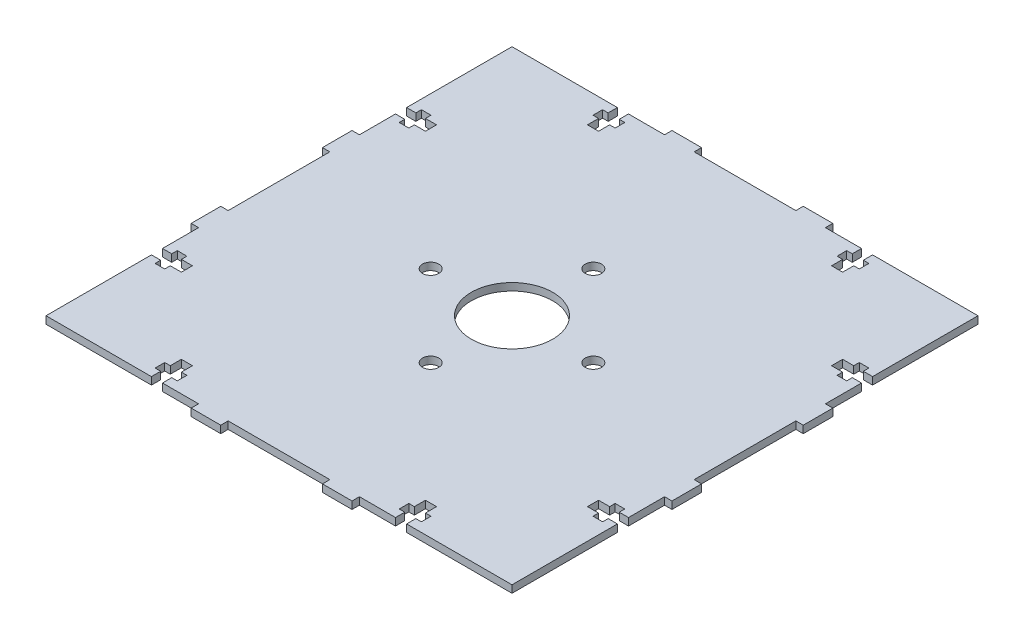
SolidWorks part; units mm, degrees
ref_plane "前视基准面" through (0, 0, 0) normal (0, 0, 1) x (1, 0, 0)
ref_plane "上视基准面" through (0, 0, 0) normal (0, 1, 0) x (1, 0, 0)
ref_plane "右视基准面" through (0, 0, 0) normal (1, 0, 0) x (0, 0, -1)
sketch "草图1" plane through (0, 0, 0) normal (0, 1, 0) x (1, 0, 0)
  line L529 (159.7547, 48.9956) -> (150.0047, 48.9956)
  line L530 (147.0047, 46.4956) -> (145.5047, 46.4956)
  line L531 (150.0047, 46.4956) -> (151.5047, 46.4956)
  line L532 (150.0047, 48.9956) -> (150.0047, 46.4956)
  line L533 (145.5047, 46.4956) -> (145.5047, 43.8956)
  line L534 (145.5047, 43.8956) -> (147.0047, 43.8956)
  line L535 (147.0047, 43.8956) -> (147.0047, 40.8956)
  line L536 (150.0047, 40.8956) -> (147.0047, 40.8956)
  line L537 (150.0047, 43.8956) -> (150.0047, 40.8956)
  line L538 (151.5047, 43.8956) -> (150.0047, 43.8956)
  line L539 (151.5047, 46.4956) -> (151.5047, 43.8956)
  line L540 (147.0047, 46.4956) -> (147.0047, 48.9956)
  line L541 (213.0047, 48.9956) -> (203.2547, 48.9956)
  line L542 (211.5047, 46.4956) -> (211.5047, 43.8956)
  line L543 (216.0047, 46.4956) -> (216.0047, 48.9956)
  line L544 (211.5047, 43.8956) -> (213.0047, 43.8956)
  line L545 (213.0047, 43.8956) -> (213.0047, 40.8956)
  line L546 (213.0047, 40.8956) -> (216.0047, 40.8956)
  line L547 (216.0047, 43.8956) -> (216.0047, 40.8956)
  line L548 (217.5047, 43.8956) -> (216.0047, 43.8956)
  line L549 (217.5047, 46.4956) -> (217.5047, 43.8956)
  line L550 (213.0047, 48.9956) -> (213.0047, 46.4956)
  line L551 (213.0047, 46.4956) -> (211.5047, 46.4956)
  line L552 (216.0047, 46.4956) -> (217.5047, 46.4956)
  line L554 (203.2547, 48.9956) -> (203.2547, 50.9956)
  line L555 (195.2547, 50.9956) -> (195.2547, 48.9956)
  line L556 (195.2547, 48.9956) -> (167.7547, 48.9956)
  line L557 (159.7547, 50.9956) -> (167.7547, 50.9956)
  line L558 (167.7547, 48.9956) -> (167.7547, 50.9956)
  line L559 (159.7547, 50.9956) -> (159.7547, 48.9956)
  line L560 (203.2547, 50.9956) -> (195.2547, 50.9956)
  line L598 (217.0047, 48.9956) -> (216.0047, 48.9956)
  line L602 (244.5047, 7.7456) -> (244.5047, 17.4956)
  line L603 (242.0047, 20.4956) -> (242.0047, 21.9956)
  line L604 (147.0047, 48.9956) -> (138.6047, 48.9956)
  line L605 (242.0047, 17.4956) -> (242.0047, 15.9956)
  line L606 (244.5047, 17.4956) -> (242.0047, 17.4956)
  line L607 (181.5047, -77.0044) -> (181.5047, -65.0044) construction
  line L608 (242.0047, 21.9956) -> (239.4047, 21.9956)
  line L609 (138.6047, 48.9956) -> (133.5047, 48.9956)
  line L613 (217.0047, 48.9956) -> (229.5047, 48.9956)
  line L614 (239.4047, 21.9956) -> (239.4047, 20.4956)
  line L615 (239.4047, 20.4956) -> (236.4047, 20.4956)
  line L616 (236.4047, 17.4956) -> (236.4047, 20.4956)
  line L617 (239.4047, 17.4956) -> (236.4047, 17.4956)
  line L618 (239.4047, 15.9956) -> (239.4047, 17.4956)
  line L619 (242.0047, 15.9956) -> (239.4047, 15.9956)
  line L620 (242.0047, 20.4956) -> (244.5047, 20.4956)
  line L621 (244.5047, -45.5044) -> (244.5047, -35.7544)
  line L622 (242.0047, -44.0044) -> (239.4047, -44.0044)
  line L623 (242.0047, -48.5044) -> (244.5047, -48.5044)
  line L624 (239.4047, -44.0044) -> (239.4047, -45.5044)
  line L625 (239.4047, -45.5044) -> (236.4047, -45.5044)
  line L626 (236.4047, -45.5044) -> (236.4047, -48.5044)
  line L627 (239.4047, -48.5044) -> (236.4047, -48.5044)
  line L628 (239.4047, -50.0044) -> (239.4047, -48.5044)
  line L629 (242.0047, -50.0044) -> (239.4047, -50.0044)
  line L630 (244.5047, -45.5044) -> (242.0047, -45.5044)
  line L631 (242.0047, -45.5044) -> (242.0047, -44.0044)
  line L632 (242.0047, -48.5044) -> (242.0047, -50.0044)
  line L633 (244.5047, -35.7544) -> (246.5047, -35.7544)
  line L634 (246.5047, -27.7544) -> (244.5047, -27.7544)
  line L635 (244.5047, -27.7544) -> (244.5047, -0.2544)
  line L636 (246.5047, 7.7456) -> (246.5047, -0.2544)
  line L637 (244.5047, -0.2544) -> (246.5047, -0.2544)
  line L638 (246.5047, 7.7456) -> (244.5047, 7.7456)
  line L639 (246.5047, -35.7544) -> (246.5047, -27.7544)
  line L640 (244.5047, -49.5044) -> (244.5047, -48.5044)
  line L641 (244.5047, 20.4956) -> (244.5047, 28.8956)
  line L642 (244.5047, 28.8956) -> (244.5047, 33.9956)
  line L643 (244.5047, -49.5044) -> (244.5047, -62.0044)
  line L644 (203.2547, -77.0044) -> (213.0047, -77.0044)
  line L645 (216.0047, -74.5044) -> (217.5047, -74.5044)
  line L646 (213.0047, -74.5044) -> (211.5047, -74.5044)
  line L647 (213.0047, -77.0044) -> (213.0047, -74.5044)
  line L648 (217.5047, -74.5044) -> (217.5047, -71.9044)
  line L649 (217.5047, -71.9044) -> (216.0047, -71.9044)
  line L650 (216.0047, -71.9044) -> (216.0047, -68.9044)
  line L651 (213.0047, -68.9044) -> (216.0047, -68.9044)
  line L652 (213.0047, -71.9044) -> (213.0047, -68.9044)
  line L653 (211.5047, -71.9044) -> (213.0047, -71.9044)
  line L654 (211.5047, -74.5044) -> (211.5047, -71.9044)
  line L655 (216.0047, -74.5044) -> (216.0047, -77.0044)
  line L656 (150.0047, -77.0044) -> (159.7547, -77.0044)
  line L657 (151.5047, -74.5044) -> (151.5047, -71.9044)
  line L658 (147.0047, -74.5044) -> (147.0047, -77.0044)
  line L659 (151.5047, -71.9044) -> (150.0047, -71.9044)
  line L660 (150.0047, -71.9044) -> (150.0047, -68.9044)
  line L661 (150.0047, -68.9044) -> (147.0047, -68.9044)
  line L662 (147.0047, -71.9044) -> (147.0047, -68.9044)
  line L663 (145.5047, -71.9044) -> (147.0047, -71.9044)
  line L664 (145.5047, -74.5044) -> (145.5047, -71.9044)
  line L665 (150.0047, -77.0044) -> (150.0047, -74.5044)
  line L666 (150.0047, -74.5044) -> (151.5047, -74.5044)
  line L667 (147.0047, -74.5044) -> (145.5047, -74.5044)
  line L668 (159.7547, -77.0044) -> (159.7547, -79.0044)
  line L669 (167.7547, -79.0044) -> (167.7547, -77.0044)
  line L670 (167.7547, -77.0044) -> (195.2547, -77.0044)
  line L671 (203.2547, -79.0044) -> (195.2547, -79.0044)
  line L672 (195.2547, -77.0044) -> (195.2547, -79.0044)
  line L673 (203.2547, -79.0044) -> (203.2547, -77.0044)
  line L674 (159.7547, -79.0044) -> (167.7547, -79.0044)
  line L675 (146.0047, -77.0044) -> (147.0047, -77.0044)
  line L676 (216.0047, -77.0044) -> (224.4047, -77.0044)
  line L677 (224.4047, -77.0044) -> (229.5047, -77.0044)
  line L678 (146.0047, -77.0044) -> (133.5047, -77.0044)
  line L679 (118.5047, -35.7544) -> (118.5047, -45.5044)
  line L680 (121.0047, -48.5044) -> (121.0047, -50.0044)
  line L681 (121.0047, -45.5044) -> (121.0047, -44.0044)
  line L682 (118.5047, -45.5044) -> (121.0047, -45.5044)
  line L683 (121.0047, -50.0044) -> (123.6047, -50.0044)
  line L684 (123.6047, -50.0044) -> (123.6047, -48.5044)
  line L685 (123.6047, -48.5044) -> (126.6047, -48.5044)
  line L686 (126.6047, -45.5044) -> (126.6047, -48.5044)
  line L687 (123.6047, -45.5044) -> (126.6047, -45.5044)
  line L688 (123.6047, -44.0044) -> (123.6047, -45.5044)
  line L689 (121.0047, -44.0044) -> (123.6047, -44.0044)
  line L690 (121.0047, -48.5044) -> (118.5047, -48.5044)
  line L691 (118.5047, 17.4956) -> (118.5047, 7.7456)
  line L692 (121.0047, 15.9956) -> (123.6047, 15.9956)
  line L693 (121.0047, 20.4956) -> (118.5047, 20.4956)
  line L694 (123.6047, 15.9956) -> (123.6047, 17.4956)
  line L695 (123.6047, 17.4956) -> (126.6047, 17.4956)
  line L696 (126.6047, 17.4956) -> (126.6047, 20.4956)
  line L697 (123.6047, 20.4956) -> (126.6047, 20.4956)
  line L698 (123.6047, 21.9956) -> (123.6047, 20.4956)
  line L699 (121.0047, 21.9956) -> (123.6047, 21.9956)
  line L700 (118.5047, 17.4956) -> (121.0047, 17.4956)
  line L701 (121.0047, 17.4956) -> (121.0047, 15.9956)
  line L702 (121.0047, 20.4956) -> (121.0047, 21.9956)
  line L703 (118.5047, 7.7456) -> (116.5047, 7.7456)
  line L704 (116.5047, -0.2544) -> (118.5047, -0.2544)
  line L705 (118.5047, -0.2544) -> (118.5047, -27.7544)
  line L706 (116.5047, -35.7544) -> (116.5047, -27.7544)
  line L707 (118.5047, -27.7544) -> (116.5047, -27.7544)
  line L708 (116.5047, -35.7544) -> (118.5047, -35.7544)
  line L709 (116.5047, 7.7456) -> (116.5047, -0.2544)
  line L710 (118.5047, 21.4956) -> (118.5047, 20.4956)
  line L711 (118.5047, -48.5044) -> (118.5047, -56.9044)
  line L712 (118.5047, -56.9044) -> (118.5047, -62.0044)
  line L713 (118.5047, 21.4956) -> (118.5047, 33.9956)
  line L714 (133.5047, 48.9956) -> (118.5047, 48.9956)
  line L715 (118.5047, 48.9956) -> (118.5047, 33.9956)
  line L716 (229.5047, 48.9956) -> (244.5047, 48.9956)
  line L717 (244.5047, 48.9956) -> (244.5047, 33.9956)
  line L718 (244.5047, -62.0044) -> (244.5047, -77.0044)
  line L719 (244.5047, -77.0044) -> (229.5047, -77.0044)
  line L720 (133.5047, -77.0044) -> (118.5047, -77.0044)
  line L721 (118.5047, -77.0044) -> (118.5047, -62.0044)
  circle A63 centre (181.5047, -14.0044) radius 22 construction
  circle A64 centre (181.5047, -14.0044) radius 11
  circle A65 centre (181.5047, -36.0044) radius 2.2
  circle A66 centre (159.5047, -14.0044) radius 2.2
  circle A67 centre (181.5047, 7.9956) radius 2.2
  circle A68 centre (203.5047, -14.0044) radius 2.2
  point P21 (235.9047, -47.5044)
  point P46 (235.9047, 18.4956)
  point P73 (148.0047, -68.4044)
  point P97 (215.0047, 40.3956)
  point P129 (149.0047, 40.3956)
  point P130 (214.0047, -68.4044)
  point P148 (127.1047, 19.4956)
  point P169 (127.1047, -46.5044)
  dimension "D2" = 22
  dimension "D1" = 44
  dimension "D4" = 4.4
  dimension "D3" = 4
extrude "凸台-拉伸1" add sketch "草图1" along normal blind 2
sketch "草图8" plane through (0, 0, -48.9956) normal (0, 0, -1) x (-1, 0, 0)
  line L0 (-213.0047, 0) -> (-216.0047, 2)
  circle A0 centre (-214.5047, 1) radius 1.5
sketch "草图9" plane through (244.5047, 0, 0) normal (1, 0, 0) x (0, 0, -1)
  line L0 (20.4956, 1) -> (17.4956, 1) construction
  line L1 (20.4956, 2) -> (20.4956, 0) construction
  line L2 (17.4956, 2) -> (17.4956, 0) construction
  circle A0 centre (18.9956, 1) radius 1.5
